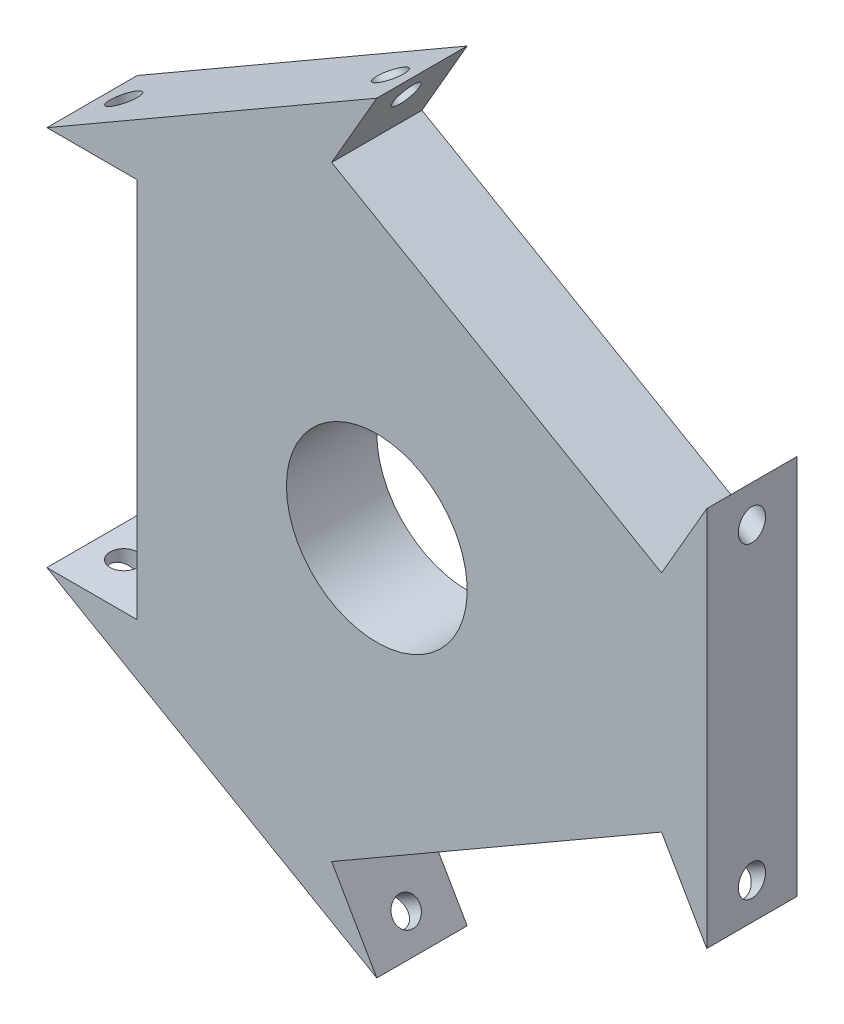
SolidWorks part; units mm, degrees
ref_plane "Front Plane" through (0, 0, 0) normal (0, 0, 1) x (1, 0, 0)
ref_plane "Top Plane" through (0, 0, 0) normal (0, 1, 0) x (1, 0, 0)
ref_plane "Right Plane" through (0, 0, 0) normal (1, 0, 0) x (0, 0, -1)
sketch "Sketch1" plane through (0, 0, 0) normal (0, 0, 1) x (1, 0, 0)
  line L0 (-36.511, 21.0796) -> (-26.511, 21.0796)
  line L7 (0, 42.1592) -> (-36.511, 21.0796)
  line L9 (-36.511, -21.0796) -> (0, -42.1592)
  line L11 (36.511, -21.0796) -> (36.511, 21.0796)
  line L13 (-26.511, 21.0796) -> (-26.511, -21.0796)
  line L14 (-26.511, -21.0796) -> (-36.511, -21.0796)
  line L15 (36.511, 21.0796) -> (31.511, 12.4194)
  line L16 (31.511, 12.4194) -> (-5, 33.499)
  line L17 (-5, 33.499) -> (0, 42.1592)
  line L18 (0, -42.1592) -> (-5, -33.499)
  line L19 (-5, -33.499) -> (31.511, -12.4194)
  line L20 (31.511, -12.4194) -> (36.511, -21.0796)
  line L21 (-36.511, 0) -> (-36.511, -21.0796) [skipped]
  line L22 (18.2555, -31.6194) -> (36.511, -21.0796) [skipped]
  line L23 (18.2555, 31.6194) -> (0, 42.1592) [skipped]
  circle A0 centre (0, 0) radius 36.511 construction
  dimension "D1" = 3
  dimension "D2" = 10
extrude "Boss-Extrude1" add sketch "Sketch1" along normal blind 10
sketch "Sketch3" plane through (0, -21.0796, 0) normal (0, 1, 0) x (1, 0, 0)
  line L1 (-36.511, -10) -> (-36.511, 0) construction
  circle A0 centre (-33.011, -5) radius 1.5
  dimension "D1" = 3
  dimension "D2" = 3.5
extrude "Cut-Extrude1" cut sketch "Sketch3" along normal through all and the other way through all
sketch "Sketch5" plane through (0, 0, 0) normal (0, 0, -1) x (-1, 0, 0)
  circle A0 centre (0, 0) radius 10
extrude "Cut-Extrude2" cut sketch "Sketch5" against normal blind 10
ref_axis "Axis2" through (0, 0, 10) along (0, 0, -1)
pattern_circular "CirPattern1" count 3 over 360 about axis through (0, 0, 10) along (0, 0, -1) of "Cut-Extrude1"
